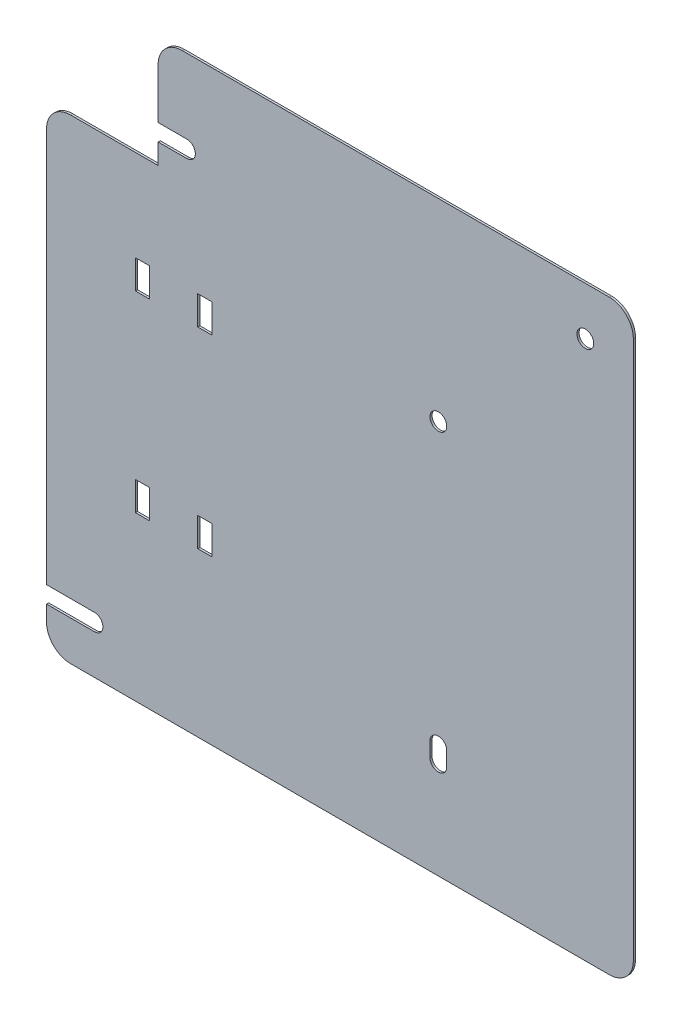
SolidWorks part; units mm, degrees
ref_plane "Front Plane" through (0, 0, 0) normal (0, 0, 1) x (1, 0, 0)
ref_plane "Top Plane" through (0, 0, 0) normal (0, 1, 0) x (1, 0, 0)
ref_plane "Right Plane" through (0, 0, 0) normal (1, 0, 0) x (0, 0, -1)
sketch "Sketch1" plane through (0, 0, 0) normal (0, 0, 1) x (1, 0, 0)
  line L0 (144, -21.75) -> (45, -21.75)
  line L1 (45, -21.75) -> (45, -45)
  line L2 (45, -45) -> (21.75, -45)
  line L3 (21.75, -45) -> (21.75, -144)
  line L4 (21.75, -144) -> (144, -144)
  line L5 (144, -144) -> (144, -21.75)
  line L6 (43, -41) -> (43, 5) construction
  line L7 (-5, -43) -> (41, -43) construction
  point P6 (134, -31.75)
  point P7 (51, -39)
  point P9 (31.75, -134)
  point P16 (103.375, -62)
  point P17 (103.375, -122)
  dimension "D1" = 10
  dimension "D2" = 10
  dimension "D3" = 2
  dimension "D4" = 2
  dimension "D5" = 10
  dimension "D6" = 10
extrude "Boss-Extrude1" add sketch "Sketch1" along normal blind 0.4445
sketch "Sketch2" plane through (0, 0, 0.4445) normal (0, 0, 1) x (1, 0, 0)
  line L0 (51, -39) -> (45, -39) construction
  line L1 (45, -21.75) -> (45, -45) construction
  line L2 (51, -40.75) -> (45, -40.75)
  line L3 (51, -37.25) -> (45, -37.25)
  line L4 (31.75, -134) -> (21.75, -134) construction
  line L5 (21.75, -45) -> (21.75, -144) construction
  line L6 (31.75, -135.75) -> (21.75, -135.75)
  line L7 (31.75, -132.25) -> (21.75, -132.25)
  line L8 (103.375, -123.5) -> (103.375, -120.5) construction
  line L9 (101.625, -123.5) -> (101.625, -120.5)
  line L10 (105.125, -123.5) -> (105.125, -120.5)
  arc A0 (51, -40.75) -> (51, -37.25) centre (51, -39) ccw
  arc A1 (45, -37.25) -> (45, -40.75) centre (45, -39) ccw
  arc A2 (31.75, -135.75) -> (31.75, -132.25) centre (31.75, -134) ccw
  arc A3 (21.75, -132.25) -> (21.75, -135.75) centre (21.75, -134) ccw
  circle A4 centre (134, -31.75) radius 1.75
  circle A5 centre (103.375, -62) radius 1.75
  arc A6 (101.625, -123.5) -> (105.125, -123.5) centre (103.375, -123.5) ccw
  arc A7 (105.125, -120.5) -> (101.625, -120.5) centre (103.375, -120.5) ccw
  circle A8 centre (103.375, -62) radius 2.25 construction
  point P5 (48, -39)
  point P10 (26.75, -134)
  point P28 (103.375, -122)
  dimension "D3" = 3.5
  dimension "D4" = 3.5
  dimension "D1" = 3.5
  dimension "D2" = 3.5
  dimension "D5" = 3.5
  dimension "D6" = 3
extrude "Cut-Extrude1" cut sketch "Sketch2" against normal through all
fillet "Fillet1" radius 5 5 edges at (45, -21.75, 0.2223) (144, -21.75, 0.2223) (144, -144, 0.2223) (21.75, -144, 0.2223) (21.75, -45, 0.2223)
sketch "Sketch3" plane through (0, 0, 0) normal (0, 0, -1) x (-1, 0, 0)
  line L0 (-48.25, -50.3307) -> (-48.25, -132.3632) construction
  line L1 (-43.25, -64) -> (-43.25, -70)
  line L2 (-56.25, -64) -> (-53.25, -64)
  line L3 (-56.25, -64) -> (-56.25, -70)
  line L4 (-56.25, -70) -> (-53.25, -70)
  line L5 (-53.25, -64) -> (-53.25, -70)
  line L6 (-40.25, -70) -> (-43.25, -70)
  line L7 (-40.25, -64) -> (-40.25, -70)
  line L8 (-40.25, -64) -> (-43.25, -64)
  line L9 (-43.25, -104) -> (-43.25, -110)
  line L10 (-56.25, -104) -> (-53.25, -104)
  line L11 (-56.25, -104) -> (-56.25, -110)
  line L12 (-56.25, -110) -> (-53.25, -110)
  line L13 (-53.25, -104) -> (-53.25, -110)
  line L14 (-40.25, -110) -> (-43.25, -110)
  line L15 (-40.25, -104) -> (-40.25, -110)
  line L16 (-40.25, -104) -> (-43.25, -104)
  line L17 (-43.25, -64) -> (-43.25, -104) construction
  line L18 (-26.75, -144) -> (-139, -144) construction
  line L20 (-21.75, -50) -> (-21.75, -132.25) construction
  dimension "D1" = 6
  dimension "D2" = 3
  dimension "D3" = 5
  dimension "D5" = 40
  dimension "D6" = 40
  dimension "D7" = 26.5
  dimension "D4" = 2
extrude "Cut-Extrude2" cut sketch "Sketch3" against normal through all
